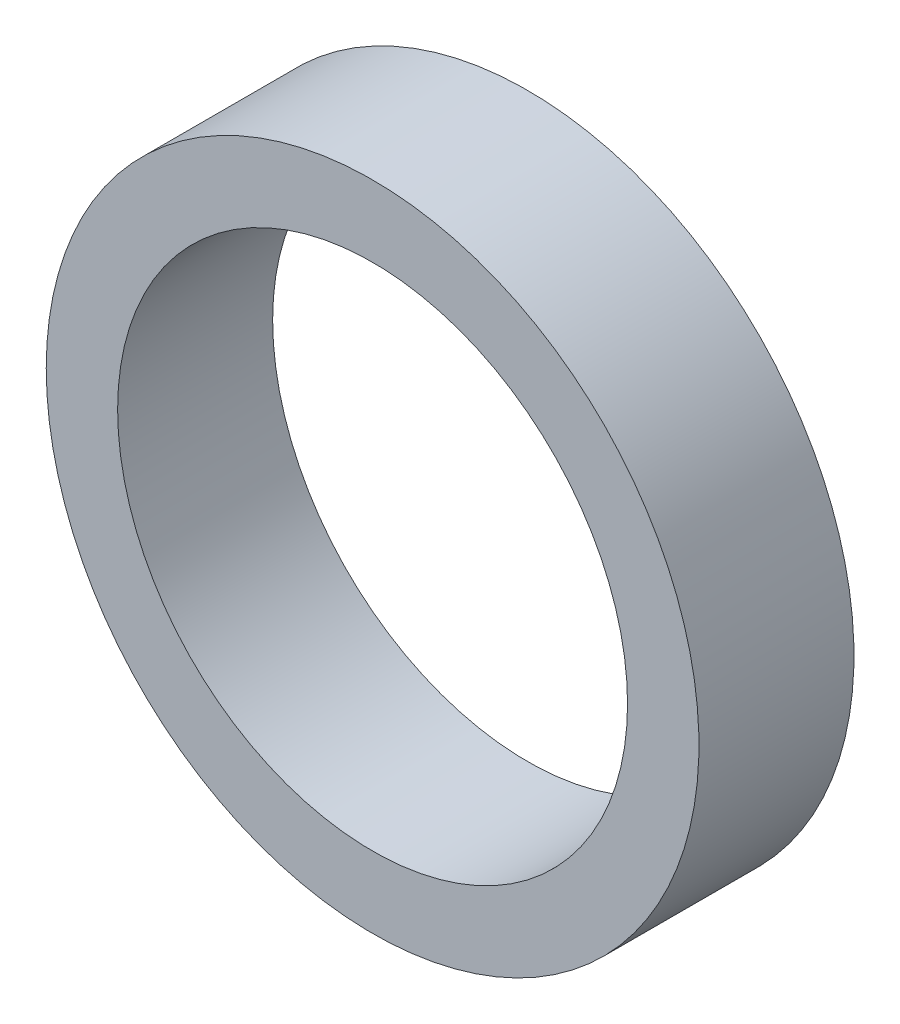
SolidWorks part; units mm, degrees
ref_plane "Plano frontal" through (0, 0, 0) normal (0, 0, 1) x (1, 0, 0)
ref_plane "Plano superior" through (0, 0, 0) normal (0, 1, 0) x (1, 0, 0)
ref_plane "Plano direito" through (0, 0, 0) normal (1, 0, 0) x (0, 0, -1)
sketch "Sketch1" plane through (0, 0, 0) normal (0, 0, 1) x (1, 0, 0)
  circle A0 centre (0, 0) radius 12.5
  circle A1 centre (0, 0) radius 16
  dimension "D1" = 25
  dimension "D2" = 32
extrude "Boss-Extrude1" add sketch "Sketch1" along normal blind 7.6
ref_point "Point1"
ref_point "Point2"
